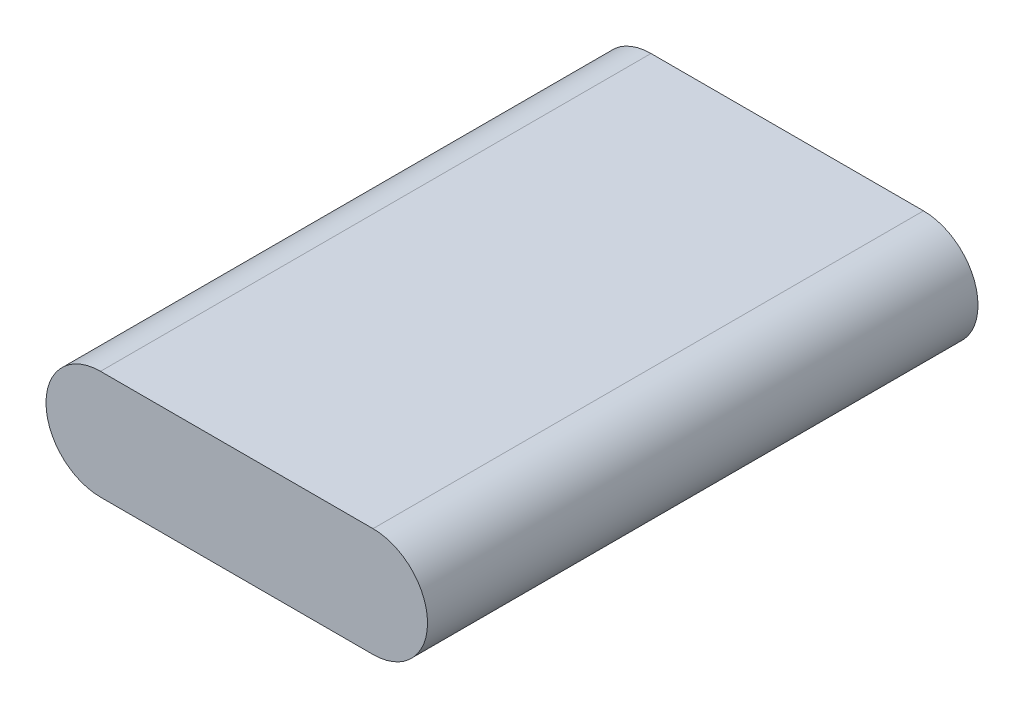
SolidWorks part; units mm, degrees
ref_plane "前视基准面" through (0, 0, 0) normal (0, 0, 1) x (1, 0, 0)
ref_plane "上视基准面" through (0, 0, 0) normal (0, 1, 0) x (1, 0, 0)
ref_plane "右视基准面" through (0, 0, 0) normal (1, 0, 0) x (0, 0, -1)
sketch "草图2" plane through (0, 0, 0) normal (0, 0, 1) x (1, 0, 0)
  line L0 (-58.637, 0) -> (38.1933, 0) construction
  line L1 (-32.805, 10) -> (17.195, 10)
  line L2 (-32.805, -10) -> (17.195, -10)
  arc A0 (-32.805, 10) -> (-32.805, -10) centre (-32.805, 0) ccw
  arc A1 (17.195, -10) -> (17.195, 10) centre (17.195, 0) ccw
  dimension "D1" = 10
  dimension "D2" = 50
extrude "凸台-拉伸2" add sketch "草图2" along normal blind 101
